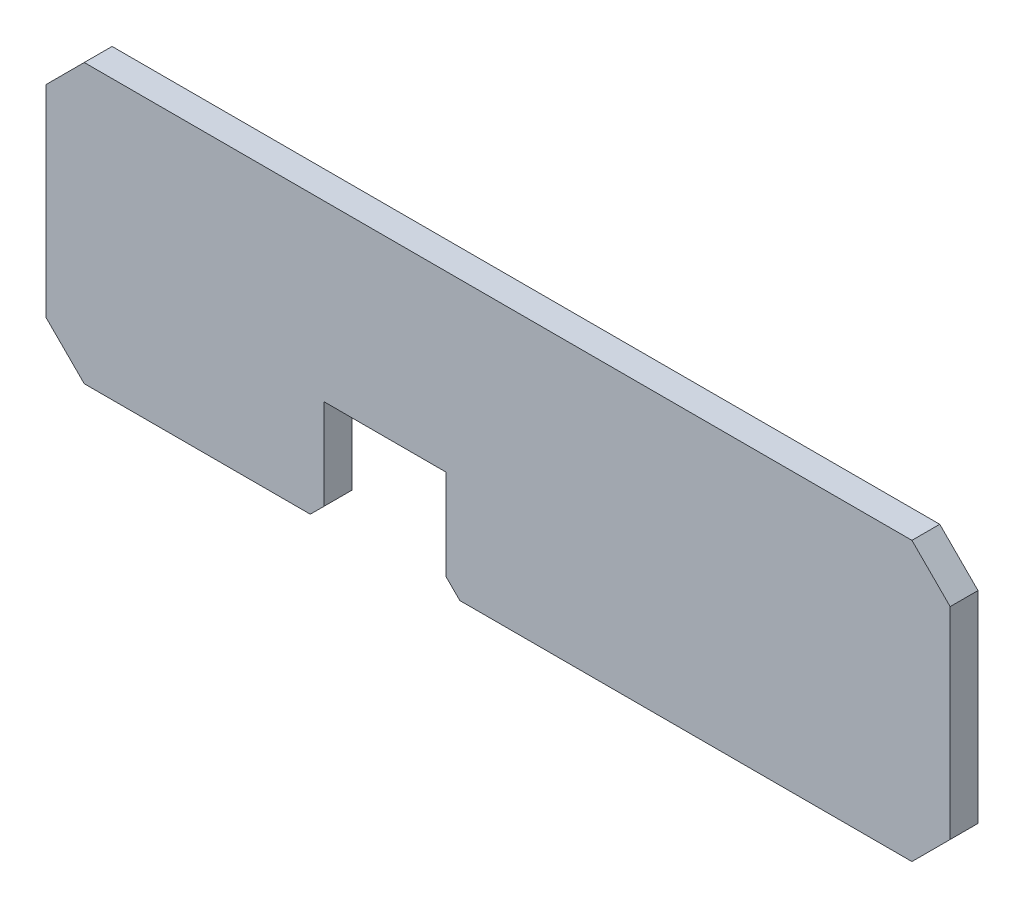
SolidWorks part; units mm, degrees
material "Plain Carbon Steel"
ref_plane "Front Plane" through (0, 0, 0) normal (0, 0, 1) x (1, 0, 0)
ref_plane "Top Plane" through (0, 0, 0) normal (0, 1, 0) x (1, 0, 0)
ref_plane "Right Plane" through (0, 0, 0) normal (1, 0, 0) x (0, 0, -1)
sketch "Sketch1" plane through (0, 0, 0) normal (0, 0, 1) x (1, 0, 0)
  line L0 (-82.55, 0) -> (82.55, 0) construction
  line L1 (-75.565, 25.4) -> (75.565, 25.4)
  line L2 (-82.55, 18.415) -> (-82.55, -18.415)
  line L3 (-75.565, -25.4) -> (-34.29, -25.4)
  line L4 (82.55, 18.415) -> (82.55, -18.415)
  line L5 (-82.55, 25.4) -> (82.55, -25.4) construction
  line L6 (-82.55, -25.4) -> (82.55, 25.4) construction
  line L7 (0, 25.4) -> (0, -25.4) construction
  line L8 (-6.985, -25.4) -> (75.565, -25.4)
  line L10 (-31.75, -22.86) -> (-31.75, -6.35)
  line L11 (-31.75, -6.35) -> (-9.525, -6.35)
  line L12 (-9.525, -22.86) -> (-9.525, -6.35)
  line L13 (-82.55, -18.415) -> (-75.565, -25.4)
  line L14 (75.565, -25.4) -> (82.55, -18.415)
  line L15 (-82.55, 18.415) -> (-75.565, 25.4)
  line L16 (75.565, 25.4) -> (82.55, 18.415)
  line L17 (-34.29, -25.4) -> (-31.75, -22.86)
  line L18 (-6.985, -25.4) -> (-9.525, -22.86)
  point P0 (0, 0)
  point P10 (-31.75, -25.4)
  point P13 (-9.525, -25.4)
  dimension "D2" = 50.8
  dimension "D3" = 92.075
  dimension "D4" = 50.8
  dimension "D5" = 19.05
  dimension "D6" = 165.1
  dimension "D7" = 50.8
  dimension "D14" = 165.1
extrude "Boss-Extrude1" add sketch "Sketch1" along normal blind 5.08
